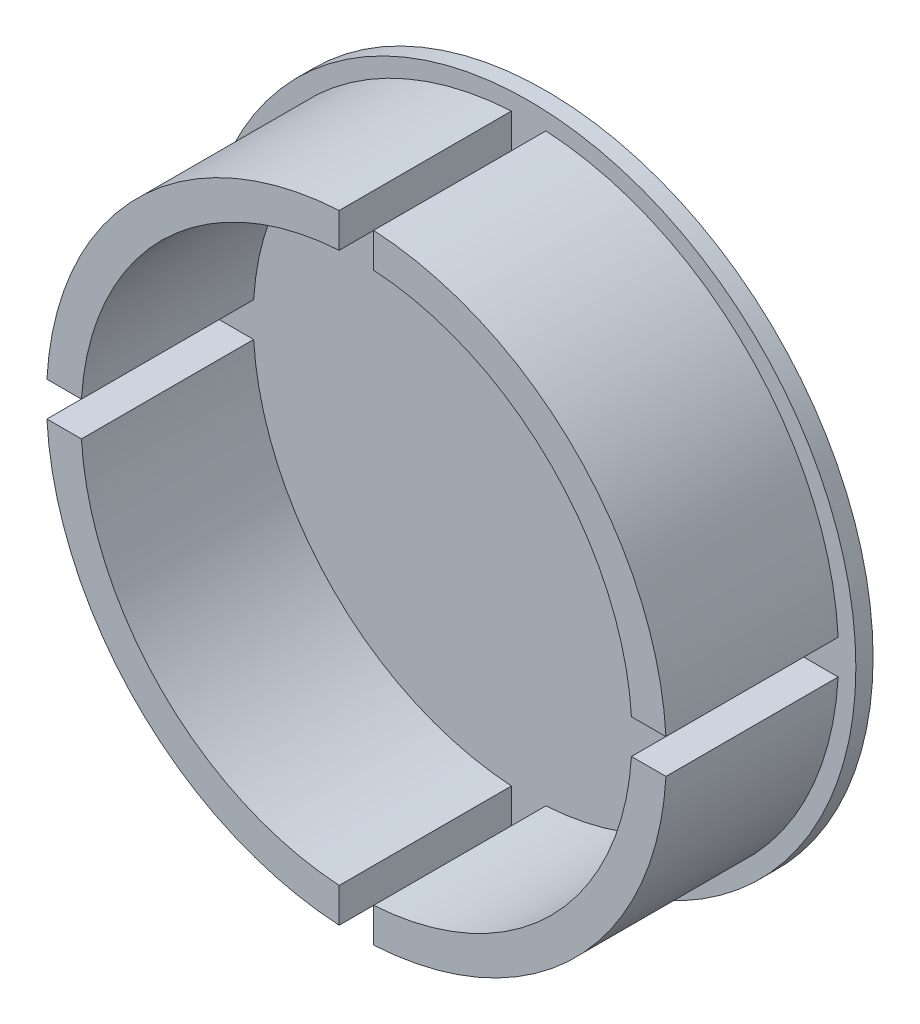
SolidWorks part; units mm, degrees
ref_plane "Front Plane" through (0, 0, 0) normal (1, 0, 0) x (0, 1, 0)
ref_plane "Top Plane" through (0, 0, 0) normal (0, 0, 1) x (0, 1, 0)
ref_plane "Right Plane" through (0, 0, 0) normal (0, 1, 0) x (-1, 0, 0)
sketch "Sketch1" plane through (0, 0, 0) normal (0, 0, 1) x (0, 1, 0)
  circle A0 centre (0, 0) radius 19
  dimension "D1" = 38
extrude "Boss-Extrude1" add sketch "Sketch1" along normal blind 1 contours A0
sketch "Sketch2" plane through (0, 0, 1) normal (0, 0, 1) x (1, 0, 0)
  circle A0 centre (0, 0) radius 18
  circle A1 centre (0, 0) radius 16
  dimension "D1" = 36
  dimension "D2" = 2
extrude "Boss-Extrude2" add sketch "Sketch2" along normal blind 10
sketch "Sketch3" plane through (0, 0, 11) normal (0, 0, 1) x (1, 0, 0)
  line L0 (0, 18) -> (0, 16) construction
  line L1 (18.5, 1) -> (18.5, -1)
  line L2 (-1, 15.5) -> (1, 15.5)
  line L3 (-1, 15.5) -> (-1, 18.5)
  line L4 (-1, 18.5) -> (1, 18.5)
  line L5 (1, 15.5) -> (1, 18.5)
  line L6 (-1, 15.5) -> (1, 18.5) construction
  line L7 (-1, 18.5) -> (1, 15.5) construction
  line L8 (15.5, -1) -> (18.5, -1)
  line L9 (15.5, 1) -> (15.5, -1)
  line L10 (15.5, 1) -> (18.5, 1)
  line L11 (1, -18.5) -> (-1, -18.5)
  line L12 (-1, -15.5) -> (-1, -18.5)
  line L13 (1, -15.5) -> (-1, -15.5)
  line L14 (1, -15.5) -> (1, -18.5)
  line L15 (-18.5, -1) -> (-18.5, 1)
  line L16 (-15.5, 1) -> (-18.5, 1)
  line L17 (-15.5, -1) -> (-15.5, 1)
  line L18 (-15.5, -1) -> (-18.5, -1)
  circle A1 centre (0, 0) radius 18 construction
  circle A2 centre (0, 0) radius 18 construction
  point P9 (0, 17)
  point P29 (0, 0)
  dimension "D1" = 2
  dimension "D2" = 3
  dimension "D3" = 4
extrude "Cut-Extrude1" cut sketch "Sketch3" against normal up to surface (10 mm away) up to face at (16, 0, 1)
